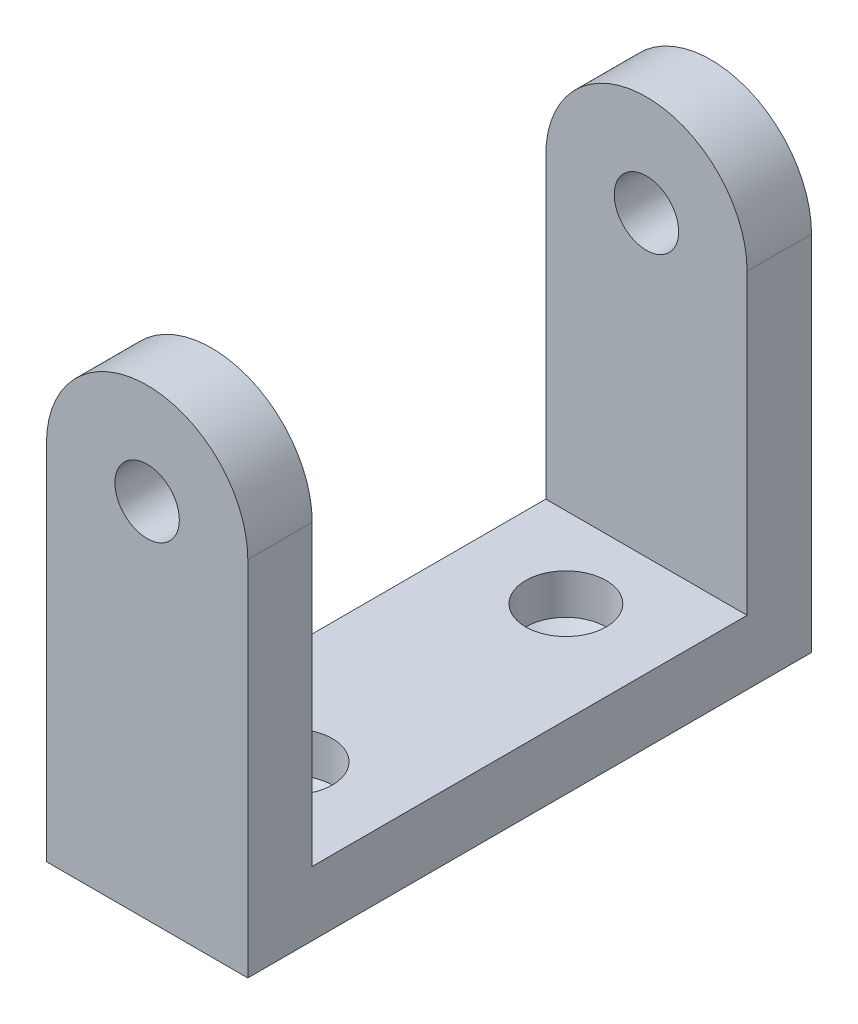
SolidWorks part; units mm, degrees
ref_plane "Front Plane" through (0, 0, 0) normal (0, 0, 1) x (1, 0, 0)
ref_plane "Top Plane" through (0, 0, 0) normal (0, 1, 0) x (1, 0, 0)
ref_plane "Right Plane" through (0, 0, 0) normal (1, 0, 0) x (0, 0, -1)
sketch "Sketch1" plane through (0, 0, 0) normal (0, 0, 1) x (1, 0, 0)
  line L2 (-12.5, 22.5) -> (-12.5, -22.5)
  line L3 (-12.5, -22.5) -> (12.5, -22.5)
  line L4 (12.5, 22.5) -> (12.5, -22.5)
  arc A0 (12.5, 22.5) -> (-12.5, 22.5) centre (0, 22.5) ccw
  circle A1 centre (0, 22.5) radius 4
  point P1 (0, 0)
  point P7 (0, 0)
  dimension "D5" = 8
  dimension "D6" = 22.5
  dimension "D1" = 45
  dimension "D3" = 25
  dimension "D4" = 12.5
extrude "Boss-Extrude1" add sketch "Sketch1" against normal blind 70
sketch "Sketch2" plane through (12.5, 0, 0) normal (1, 0, 0) x (0, 0, -1)
  line L1 (62, 35) -> (8, 35)
  line L2 (62, 35) -> (62, -14.5)
  line L4 (8, 35) -> (8, -14.5)
  line L5 (70, -22.5) -> (0, -22.5) construction
  line L7 (70, 35) -> (0, 35) construction
  line L8 (70, -22.5) -> (70, 22.5) construction
  line L9 (0, -22.5) -> (0, 22.5) construction
  line L10 (8, -14.5) -> (62, -14.5)
  point P0 (35, 6.25)
  dimension "D1" = 0
  dimension "D2" = 8
  dimension "D3" = 8
  dimension "D4" = 8
extrude "Cut-Extrude1" cut sketch "Sketch2" against normal mid plane 70
hole_wizard "Hole1" positions "Sketch4" profile "Sketch5" legacy end condition up to next
sketch "Sketch4" plane through (0, -14.5, 0) normal (0, 1, 0) x (1, 0, 0)
  line L0 (12.5, 70) -> (-12.5, 70) construction
  point P0 (0, 52)
  point P2 (0, 18)
  dimension "D1" = 34
  dimension "D2" = 18
sketch "Sketch5" plane through (0, -14.5, -52) normal (1, 0, 0) x (0, 0, 1)
  line L0 (0, 0) -> (0, 8)
  line L1 (0, 8) -> (3, 8)
  line L2 (3, 8) -> (3, 6.2017)
  line L3 (3, 6.2017) -> (5, 5)
  line L4 (5, 5) -> (5, 0)
  line L5 (5, 0) -> (0, 0)
  line L6 (0, -6.13) -> (0, 109.2824) construction
  line L7 (-3, 6.2017) -> (-5, 5) construction
  line L8 (0, 8) -> (-3, 8) construction
  dimension "Diameter" = 6
  dimension "Depth" = 8
  dimension "C-Drill Diameter" = 10
  dimension "C-Drill Depth" = 5
  dimension "C-Drill Angle" = 118
